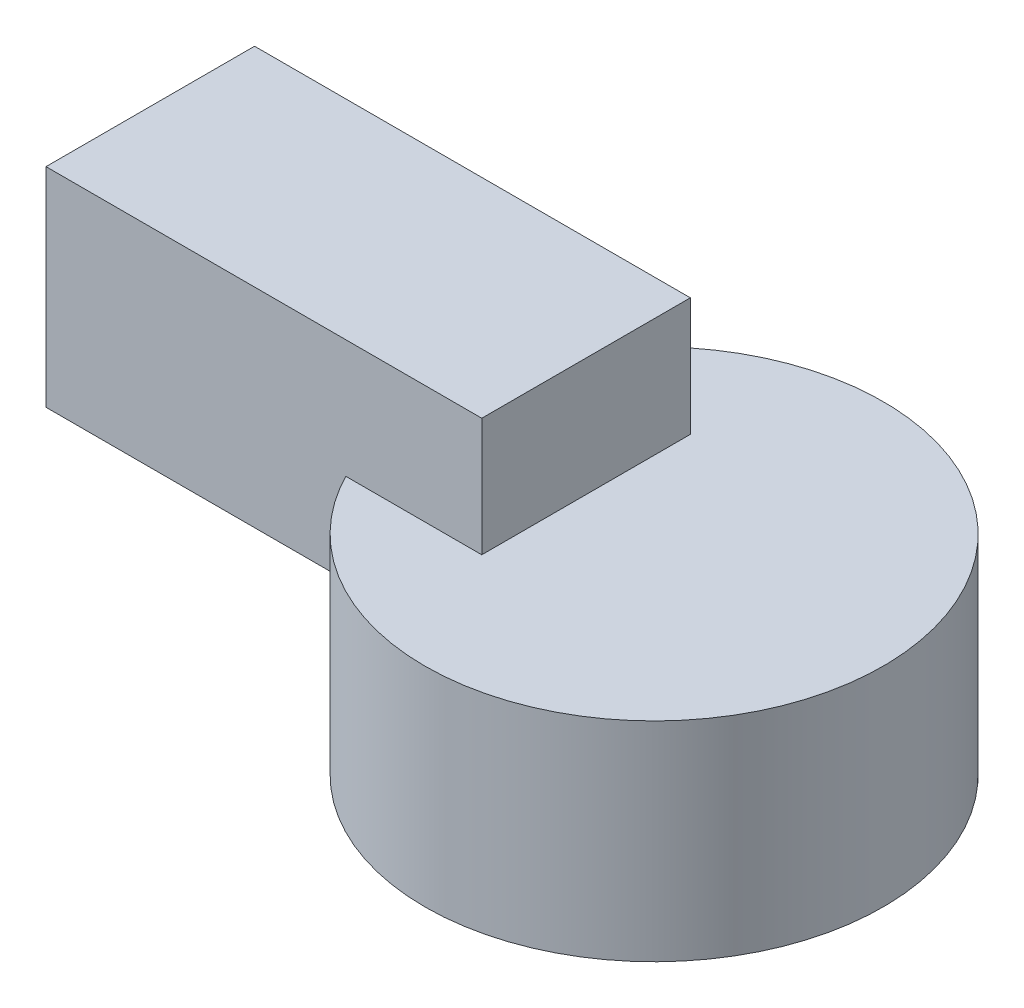
SolidWorks part; units mm, degrees
ref_plane "Front Plane" through (0, 0, 0) normal (0, 0, 1) x (1, 0, 0)
ref_plane "Top Plane" through (0, 0, 0) normal (0, 1, 0) x (1, 0, 0)
ref_plane "Right Plane" through (0, 0, 0) normal (1, 0, 0) x (0, 0, -1)
sketch "Sketch1" plane through (0, 0, 0) normal (0, 1, 0) x (1, 0, 0)
  circle A0 centre (0, 0) radius 27.9039
extrude "Boss-Extrude1" add sketch "Sketch1" along normal mid plane 25.4
sketch "Sketch2" plane through (0, 0, 0) normal (0, 0, 1) x (1, 0, 0)
  line L1 (-61.3546, 27.104) -> (-8.2867, 27.104)
  line L2 (-61.3546, 27.104) -> (-61.3546, 1.7217)
  line L3 (-61.3546, 1.7217) -> (-8.2867, 1.7217)
  line L4 (-8.2867, 27.104) -> (-8.2867, 1.7217)
  line L5 (-61.3546, 27.104) -> (-8.2867, 1.7217) construction
  line L6 (-61.3546, 1.7217) -> (-8.2867, 27.104) construction
  point P0 (-34.8206, 14.4129)
extrude "Boss-Extrude2" add sketch "Sketch2" along normal mid plane 25.4 separate body
